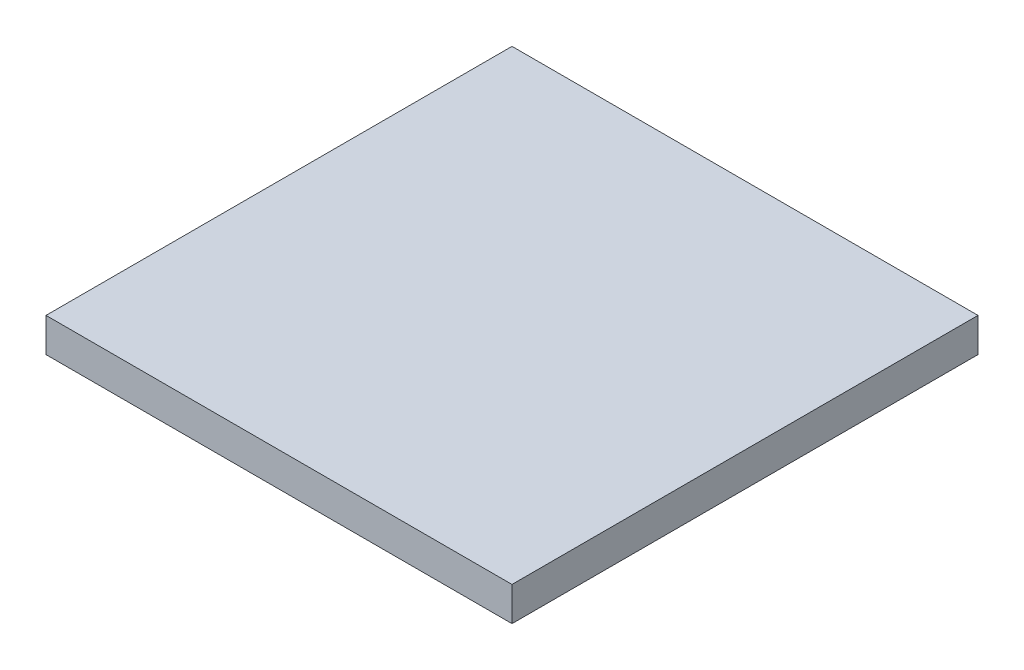
SolidWorks part; units mm, degrees
ref_plane "Front Plane" through (0, 0, 0) normal (0, 0, 1) x (1, 0, 0)
ref_plane "Top Plane" through (0, 0, 0) normal (0, 1, 0) x (1, 0, 0)
ref_plane "Right Plane" through (0, 0, 0) normal (1, 0, 0) x (0, 0, -1)
sketch "Sketch1" plane through (0, 0, 0) normal (0, 0, 1) x (1, 0, 0)
  line L7 (-76.2, -5.5563) -> (76.2, -5.5563)
  line L8 (-76.2, -5.5563) -> (-76.2, 5.5562)
  line L9 (-76.2, 5.5562) -> (76.2, 5.5562)
  line L10 (76.2, -5.5563) -> (76.2, 5.5562)
  line L11 (-76.2, -5.5563) -> (76.2, 5.5562) construction
  line L12 (-76.2, 5.5562) -> (76.2, -5.5563) construction
  point P4 (0, 0)
  point P14 (0, 0)
  dimension "Thickness" = 11.1125
  dimension "Width" = 152.4
sketch "Sketch2" plane through (0, 0, 0) normal (0, 1, 0) x (0, 0, -1)
  line L0 (76.2, 76.2) -> (-76.2, 76.2) construction
  point P4 (0, 76.2)
  dimension "Length" = 152.4
sketch "Sketch3" plane through (0, 0, 0) normal (0, 0, 1) x (1, 0, 0)
  line L6 (-76.2, 5.5562) -> (76.2, 5.5562)
  line L7 (76.2, 5.5562) -> (76.2, -5.5563)
  line L8 (76.2, -5.5563) -> (-76.2, -5.5563)
  line L9 (-76.2, -5.5563) -> (-76.2, 5.5562)
extrude "Boss-Extrude1" add sketch "Sketch3" along normal mid plane 152.4
equation "\"D1@Boss-Extrude1\" = \"Length@Sketch2\""
